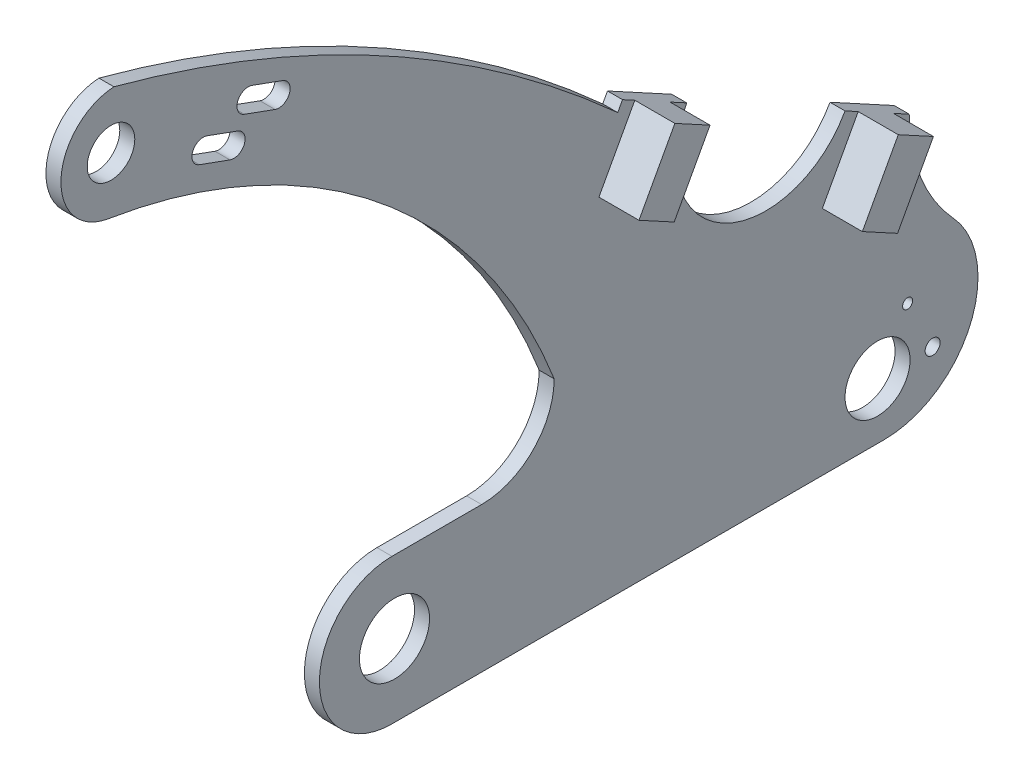
SolidWorks part; units mm, degrees
material "AISI 1020"
ref_plane "Front Plane" through (0, 0, 0) normal (0, 0, 1) x (1, 0, 0)
ref_plane "Top Plane" through (0, 0, 0) normal (0, 1, 0) x (1, 0, 0)
ref_plane "Right Plane" through (0, 0, 0) normal (1, 0, 0) x (0, 0, -1)
sketch "Sketch1" plane through (0, 0, 0) normal (1, 0, 0) x (0, 0, -1)
  line L0 (-49.1593, 0) -> (49.1593, 0)
  line L1 (49.1593, 37.5) -> (41.1593, 37.5) construction
  line L2 (-49.1593, 29) -> (-31.2593, 29)
  line L3 (0, -31.4761) -> (0, 31.4761) construction
  line L4 (-104.7059, 138) -> (-37.7059, 138) construction
  line L5 (32.1487, 42.1907) -> (-34.9377, 138) construction
  line L6 (45.8407, 11.2423) -> (47.8407, 11.2423) construction
  line L7 (45.8407, 15.7423) -> (47.8407, 15.7423)
  line L8 (45.8407, 6.7423) -> (47.8407, 6.7423)
  line L9 (-104.7059, 138) -> (-105.873, 115.7306) construction
  line L10 (-105.2895, 126.8653) -> (-115.2758, 127.3886) construction
  line L11 (-16.7593, 43.5) -> (-24.2593, 56.4904) construction
  line L12 (59.6251, 11.2423) -> (61.3276, 11.2423) construction
  line L13 (-49.478, 14.5) -> (-46.5284, 14.5) construction
  line L14 (-48.29, 14.5) -> (-46.0777, 14.5) construction
  line L15 (-86.8655, 118.0957) -> (-80.7575, 115.8726) construction
  line L16 (-86.096, 120.21) -> (-79.988, 117.9869)
  line L17 (-87.6351, 115.9814) -> (-81.5271, 113.7583)
  line L18 (-87.841, 113.2563) -> (-77.7033, 113.2563) construction
  line L19 (-77.8737, 122.3244) -> (-71.7657, 120.1012) construction
  line L20 (-77.1041, 124.4387) -> (-70.9961, 122.2155)
  line L21 (-78.6432, 120.21) -> (-72.5352, 117.9869)
  line L22 (-80.7575, 117.9869) -> (-78.616, 117.9869) construction
  line L23 (-72.7481, 117.9869) -> (-70.635, 117.9869) construction
  line L24 (41.3407, 60.8) -> (9.7153, 78) construction
  line L25 (9.7153, 78) -> (-3.1105, 84.9756)
  line L26 (41.3407, 60.8) -> (54.1665, 53.8244)
  line L28 (-3.1105, 84.9756) -> (-4.066, 83.2186)
  arc A3 (-49.1593, 0) -> (-49.1593, 29) centre (-49.1593, 14.5) cw
  arc A4 (62.9185, 31.4877) -> (49.1593, 0) centre (49.1593, 18.75) cw
  arc A5 (41.1593, 37.5) -> (32.1487, 42.1907) centre (41.1593, 48.5) cw construction
  arc A6 (32.1487, 42.1907) -> (25.3729, 51.4007) centre (-167.8609, -97.8576) ccw construction
  arc A7 (-16.7593, 43.5) -> (-31.2593, 29) centre (-31.2593, 43.5) cw
  arc A12 (-104.7059, 138) -> (-105.873, 115.7306) centre (-104.075, 126.8016) ccw
  arc A13 (-105.873, 115.7306) -> (-16.7593, 43.5) centre (-124.3727, 1.8199) cw
  circle A14 centre (58.8407, 11.2423) radius 1.5
  arc A15 (45.8407, 15.7423) -> (45.8407, 6.7423) centre (45.8407, 11.2423) ccw
  arc A16 (47.8407, 6.7423) -> (47.8407, 15.7423) centre (47.8407, 11.2423) ccw
  circle A17 centre (53.8407, 21.2423) radius 1
  circle A18 centre (-48.6593, 14.5) radius 7
  circle A19 centre (-105.2895, 126.8653) radius 4.75
  arc A20 (-86.096, 120.21) -> (-87.6351, 115.9814) centre (-86.8655, 118.0957) ccw
  arc A21 (-81.5271, 113.7583) -> (-79.988, 117.9869) centre (-80.7575, 115.8726) ccw
  arc A22 (-77.1041, 124.4387) -> (-78.6432, 120.21) centre (-77.8737, 122.3244) ccw
  arc A23 (-72.5352, 117.9869) -> (-70.9961, 122.2155) centre (-71.7657, 120.1012) ccw
  arc A24 (9.7153, 78) -> (41.3407, 60.8) centre (25.528, 69.4) ccw
  arc A25 (54.1665, 53.8244) -> (62.9185, 31.4877) centre (87.0463, 53.8244) ccw
  arc A26 (-4.066, 83.2186) -> (-104.7059, 138) centre (-167.8609, -97.8576) ccw
  point P2 (-63.6593, 14.5)
  point P3 (66.3407, 11.2423)
  point P5 (0, 0)
  point P14 (0, 0)
  point P26 (46.8407, 11.2423)
  point P34 (-115.2758, 127.3886)
  point P39 (41.3407, 11.2423)
  point P40 (52.3407, 11.2423)
  point P53 (-83.8115, 116.9842)
  point P60 (-88.9799, 118.8653)
  point P61 (-78.6432, 115.1031)
  point P64 (-74.8197, 121.2128)
  point P71 (-79.988, 123.0939)
  point P72 (-69.6514, 119.3317)
  point P77 (-75.5892, 119.0985)
  dimension "D4" = 11
  dimension "D3" = 14.5
  dimension "D1" = 130
  dimension "D2" = 18.75
  dimension "D8" = 14.5
  dimension "D15" = 22.3
  dimension "D17" = 93
  dimension "D18" = 15
  dimension "D11" = 3
  dimension "D16" = 11
  dimension "D21" = 2
  dimension "D24" = 14
  dimension "D26" = 9.5
  dimension "D34" = 36
  dimension "D5" = 8
  dimension "D6" = 125
  dimension "D7" = 138
  dimension "D9" = 67
  dimension "D10" = 32.4
  dimension "D12" = 10
  dimension "D13" = 7.5
  dimension "D14" = 14.5
  dimension "D19" = 9
  dimension "D20" = 14
  dimension "D22" = 12.5
  dimension "D23" = 10
  dimension "D25" = 15
  dimension "D27" = 11
  dimension "D28" = 4.5
  dimension "D29" = 20
  dimension "D30" = 16.3096
  dimension "D31" = 8
  dimension "D32" = 11
  dimension "D33" = 4.5
  dimension "D35" = 60.8
  dimension "D36" = 78
  dimension "D37" = 14.6
  dimension "D38" = 2
extrude "Boss-Extrude1" add sketch "Sketch1" along normal blind 3
sketch "Sketch2" plane through (3, 0, 0) normal (1, 0, 0) x (0, 0, -1)
  line L0 (54.1665, 53.8244) -> (41.3407, 60.8) construction
  line L1 (43.9761, 59.3667) -> (51.0039, 55.5444)
  line L2 (43.9761, 59.3667) -> (36.8094, 46.1895)
  line L3 (36.8094, 46.1895) -> (43.8373, 42.3672)
  line L4 (51.0039, 55.5444) -> (43.8373, 42.3672)
  line L5 (9.7153, 78) -> (-3.1105, 84.9756) construction
  line L6 (-0.6507, 83.6378) -> (6.3771, 79.8156)
  line L7 (-0.6507, 83.6378) -> (-7.8174, 70.4606)
  line L8 (-7.8174, 70.4606) -> (-0.7895, 66.6383)
  line L9 (6.3771, 79.8156) -> (-0.7895, 66.6383)
  arc A0 (9.7153, 78) -> (41.3407, 60.8) centre (25.528, 69.4) ccw construction
  arc A1 (9.7153, 78) -> (41.3407, 60.8) centre (25.528, 69.4) ccw construction
  dimension "D1" = 8
  dimension "D2" = 15
  dimension "D3" = 3
  dimension "D4" = 3.8
extrude "Boss-Extrude2" add sketch "Sketch2" along normal blind 8
sketch "Sketch4" plane through (3, 0, 0) normal (1, 0, 0) x (0, 0, -1)
  circle A0 centre (47.8407, 11.2423) radius 6.5
  dimension "D1" = 13
extrude "Cut-Extrude1" cut sketch "Sketch4" against normal blind 10
